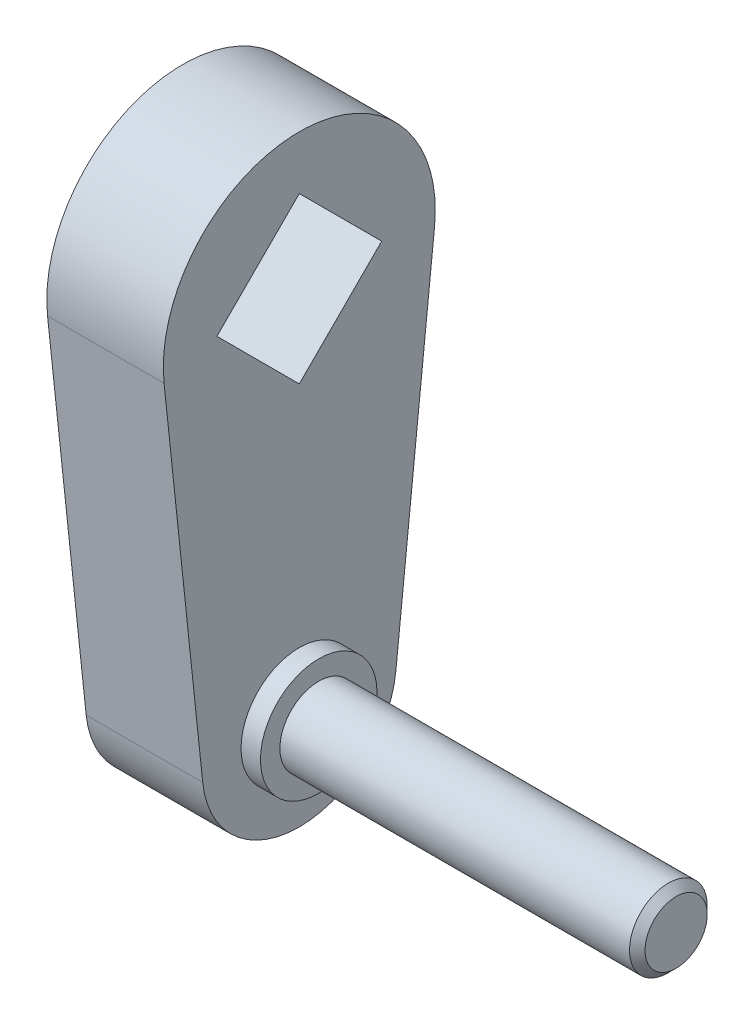
SolidWorks part; units mm, degrees
ref_plane "前视基准面" through (0, 0, 0) normal (0, 0, 1) x (1, 0, 0)
ref_plane "上视基准面" through (0, 0, 0) normal (0, 1, 0) x (1, 0, 0)
ref_plane "右视基准面" through (0, 0, 0) normal (1, 0, 0) x (0, 0, -1)
sketch "草图4" plane through (0, 0, 0) normal (1, 0, 0) x (0, 0, -1)
  line L0 (-34.8056, -3.6842) -> (-24.8611, -97.6316)
  line L1 (34.8056, -3.6842) -> (24.8611, -97.6316)
  line L2 (0, 21.2132) -> (21.2132, 0)
  line L3 (21.2132, 0) -> (0, -21.2132)
  line L4 (0, -21.2132) -> (-21.2132, 0)
  line L5 (-21.2132, 0) -> (0, 21.2132)
  arc A0 (-34.8056, -3.6842) -> (34.8056, -3.6842) centre (0, 0) cw
  arc A1 (-24.8611, -97.6316) -> (24.8611, -97.6316) centre (0, -95) ccw
  circle A2 centre (0, -95) radius 10
  dimension "D1" = 35
  dimension "D3" = 25
  dimension "D4" = 20
  dimension "D2" = 95
  dimension "D5" = 30
extrude "凸台-拉伸4" add sketch "草图4" against normal blind 30
sketch "草图5" plane through (0, 0, 0) normal (1, 0, 0) x (0, 0, -1)
  circle A0 centre (0, -95) radius 10
  circle A1 centre (0, -95) radius 10 construction
extrude "凸台-拉伸5" add sketch "草图5" against normal blind 28
sketch "草图6" plane through (0, 0, 0) normal (1, 0, 0) x (0, 0, -1)
  circle A0 centre (0, -95) radius 15
  arc A1 (-24.8611, -97.6316) -> (24.8611, -97.6316) centre (0, -95) ccw construction
  dimension "D1" = 30
extrude "凸台-拉伸6" add sketch "草图6" along normal blind 5
sketch "草图7" plane through (5, 0, 0) normal (1, 0, 0) x (0, 0, -1)
  circle A0 centre (0, -95) radius 10
  dimension "D1" = 20
extrude "凸台-拉伸7" add sketch "草图7" along normal blind 92
chamfer "倒角2" distance 2 angle 45 1 edges at (97, -95, -10)
